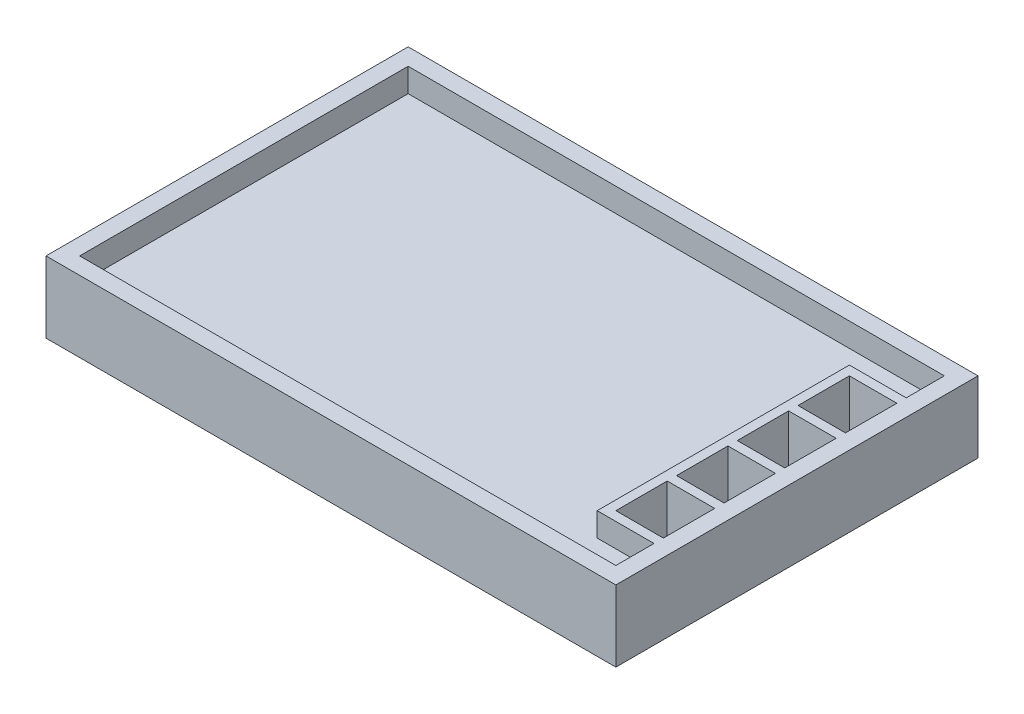
SolidWorks part; units mm, degrees
ref_plane "Front Plane" through (0, 0, 0) normal (0, 0, 1) x (1, 0, 0)
ref_plane "Top Plane" through (0, 0, 0) normal (0, 1, 0) x (1, 0, 0)
ref_plane "Right Plane" through (0, 0, 0) normal (1, 0, 0) x (0, 0, -1)
sketch "Sketch1" plane through (0, 0, 0) normal (0, 1, 0) x (1, 0, 0)
  line L1 (-272.4428, 268.4165) -> (337.1572, 268.4165)
  line L2 (-272.4428, 268.4165) -> (-272.4428, -118.9835)
  line L3 (-272.4428, -118.9835) -> (337.1572, -118.9835)
  line L4 (337.1572, 268.4165) -> (337.1572, -118.9835)
  dimension "D1" = 609.6
  dimension "D2" = 387.4
extrude "Boss-Extrude1" add sketch "Sketch1" against normal blind 76.2
sketch "Sketch2" plane through (0, 0, 0) normal (0, 1, 0) x (1, 0, 0)
  line L0 (-272.4428, 268.4165) -> (-272.4428, -118.9835) construction
  line L1 (-254.4428, 250.4165) -> (319.1572, 250.4165)
  line L2 (-254.4428, 250.4165) -> (-254.4428, -100.9835)
  line L3 (-254.4428, -100.9835) -> (319.1572, -100.9835)
  line L4 (319.1572, 250.4165) -> (319.1572, -100.9835)
  line L5 (-272.4428, -118.9835) -> (337.1572, -118.9835) construction
  line L6 (337.1572, -118.9835) -> (337.1572, 268.4165) construction
  line L7 (337.1572, 268.4165) -> (-272.4428, 268.4165) construction
  dimension "D1" = 18
  dimension "D2" = 18
  dimension "D3" = 18
  dimension "D4" = 18
extrude "Cut-Extrude1" cut sketch "Sketch2" against normal offset from surface (25.4 mm away) 25.4 up to face at (32.3572, 0, -74.7165)
sketch "Sketch3" plane through (0, -25.4, 0) normal (0, 1, 0) x (1, 0, 0)
  line L0 (384.8029, 74.7165) -> (-352.974, 74.7165) construction
  line L1 (-254.4428, 250.4165) -> (319.1572, 250.4165) construction
  line L2 (-254.4428, -100.9835) -> (319.1572, -100.9835) construction
  line L3 (319.1572, 250.4165) -> (319.1572, -100.9835) construction
  line L4 (319.1572, 199.6165) -> (268.3572, 199.6165)
  line L5 (319.1572, 199.6165) -> (319.1572, 144.6665)
  line L6 (319.1572, 144.6665) -> (268.3572, 144.6665)
  line L7 (268.3572, 199.6165) -> (268.3572, 144.6665)
  line L8 (319.1572, -100.9835) -> (319.1572, 250.4165) construction
  line L9 (319.1572, 134.6665) -> (268.3572, 134.6665)
  line L10 (319.1572, 134.6665) -> (319.1572, 79.7165)
  line L11 (319.1572, 79.7165) -> (268.3572, 79.7165)
  line L12 (268.3572, 134.6665) -> (268.3572, 79.7165)
  line L13 (319.1572, 69.7165) -> (268.3572, 69.7165)
  line L14 (319.1572, 69.7165) -> (319.1572, 14.7665)
  line L15 (319.1572, 14.7665) -> (268.3572, 14.7665)
  line L16 (268.3572, 69.7165) -> (268.3572, 14.7665)
  line L18 (319.1572, 4.7665) -> (268.3572, 4.7665)
  line L19 (319.1572, 4.7665) -> (319.1572, -50.1835)
  line L20 (319.1572, -50.1835) -> (268.3572, -50.1835)
  line L21 (268.3572, 4.7665) -> (268.3572, -50.1835)
  dimension "D1" = 10
  dimension "D2" = 10
  dimension "D3" = 10
  dimension "D4" = 50.8
  dimension "D5" = 50.8
extrude "Cut-Extrude2" cut sketch "Sketch3" against normal offset from surface (35.8 mm away) 15 up to face at (32.3572, -76.2, -74.7165)
sketch "Sketch7" plane through (0, -25.4, 0) normal (0, 1, 0) x (1, 0, 0)
  line L0 (319.1572, 209.6165) -> (258.3572, 209.6165)
  line L1 (319.1572, 250.4165) -> (319.1572, 199.6165) construction
  line L2 (258.3572, 209.6165) -> (258.3572, -60.1835)
  line L3 (258.3572, -60.1835) -> (319.1572, -60.1835)
  line L4 (319.1572, -50.1835) -> (319.1572, -100.9835) construction
  line L5 (319.1572, -60.1835) -> (319.1572, -50.1835)
  line L6 (319.1572, -50.1835) -> (268.3572, -50.1835)
  line L7 (268.3572, -50.1835) -> (268.3572, 4.7665)
  line L8 (268.3572, 4.7665) -> (319.1572, 4.7665)
  line L9 (319.1572, 4.7665) -> (319.1572, 14.7665)
  line L10 (319.1572, 14.7665) -> (268.3572, 14.7665)
  line L11 (268.3572, 14.7665) -> (268.3572, 69.7165)
  line L12 (268.3572, 69.7165) -> (319.1572, 69.7165)
  line L13 (319.1572, 69.7165) -> (319.1572, 79.7165)
  line L14 (319.1572, 79.7165) -> (268.3572, 79.7165)
  line L15 (268.3572, 79.7165) -> (268.3572, 134.6665)
  line L16 (268.3572, 134.6665) -> (319.1572, 134.6665)
  line L17 (319.1572, 134.6665) -> (319.1572, 144.6665)
  line L18 (319.1572, 144.6665) -> (268.3572, 144.6665)
  line L19 (268.3572, 144.6665) -> (268.3572, 199.6165)
  line L20 (268.3572, 199.6165) -> (319.1572, 199.6165)
  line L21 (319.1572, 199.6165) -> (319.1572, 209.6165)
  dimension "D1" = 10
  dimension "D2" = 10
  dimension "D3" = 10
extrude "Boss-Extrude2" add sketch "Sketch7" along normal up to surface (25.4 mm away) up to face at (32.3572, 0, -74.7165)
